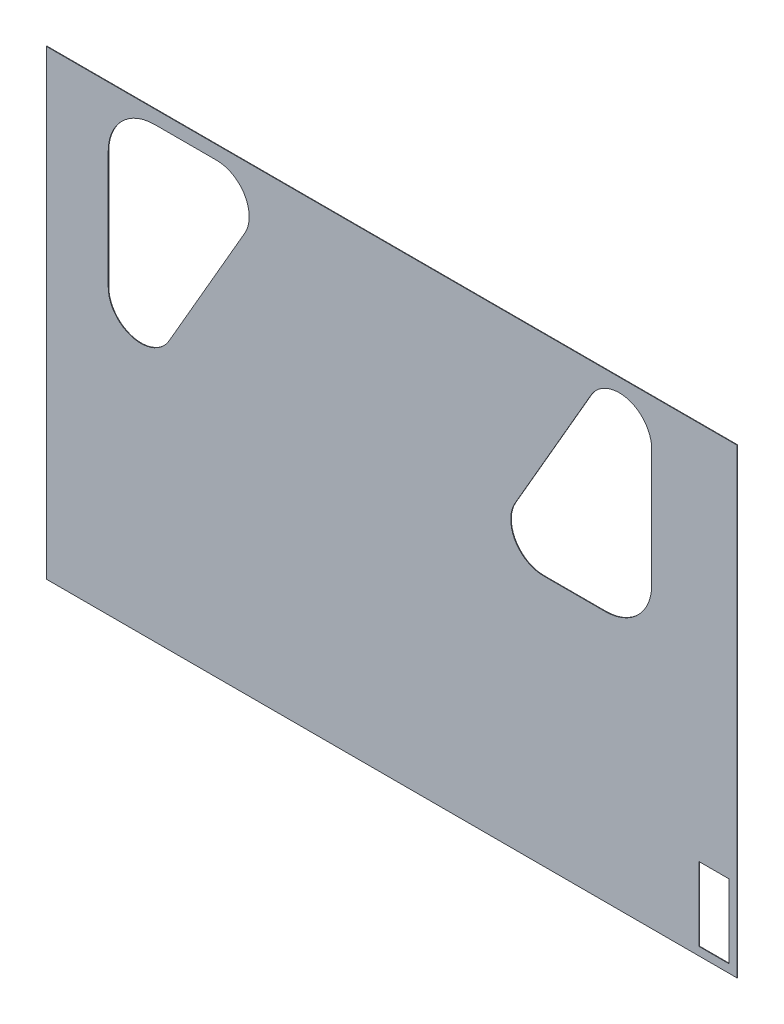
SolidWorks part; units mm, degrees
ref_plane "Front Plane" through (0, 0, 0) normal (0, 0, 1) x (1, 0, 0)
ref_plane "Top Plane" through (0, 0, 0) normal (0, 1, 0) x (1, 0, 0)
ref_plane "Right Plane" through (0, 0, 0) normal (1, 0, 0) x (0, 0, -1)
sketch "Sketch1" plane through (0, 0, 0) normal (0, 0, 1) x (1, 0, 0)
  line L1 (0, 0) -> (2500, 0)
  line L2 (0, 0) -> (0, 1670)
  line L3 (0, 1670) -> (2500, 1670)
  line L4 (2500, 0) -> (2500, 1670)
  line L5 (2470, 30) -> (2361.56, 30)
  line L6 (2470, 30) -> (2470, 296)
  line L7 (2470, 296) -> (2361.56, 296)
  line L8 (2361.56, 30) -> (2361.56, 296)
  dimension "D1" = 2500
  dimension "D2" = 1670
  dimension "D3" = 30
  dimension "D4" = 30
  dimension "D5" = 108.44
  dimension "D6" = 266
extrude "Boss-Extrude1" add sketch "Sketch1" along normal blind 2
extrude "Cut-Extrude1" cut sketch "Sketch2" against normal through all
sketch "Sketch2" plane through (471.9635, -531.6168, 33) normal (0, 0, 1) x (1, 0, 0)
  line L0 (1498.8454, 2093.6165) -> (1224.6054, 1618.6165)
  line L1 (1326.7965, 1441.6168) -> (1551.0365, 1441.6168)
  line L2 (1719.0365, 1609.6168) -> (1719.0365, 2034.6168)
  line L5 (-247.9635, 1984.6168) -> (-247.9635, 1559.6168)
  line L6 (-27.7724, 1500.617) -> (246.4676, 1975.617)
  line L7 (144.2765, 2152.6168) -> (-79.9635, 2152.6168)
  arc A0 (1551.0365, 1441.6168) -> (1719.0365, 1609.6168) centre (1551.0365, 1609.6168) ccw
  arc A1 (1498.8454, 2093.6165) -> (1719.0365, 2034.6168) centre (1601.0365, 2034.6168) cw
  arc A2 (1224.6054, 1618.6165) -> (1326.7965, 1441.6168) centre (1326.7965, 1559.6168) ccw
  arc A3 (-247.9635, 1559.6168) -> (-27.7724, 1500.617) centre (-129.9635, 1559.6168) ccw
  arc A4 (246.4676, 1975.617) -> (144.2765, 2152.6168) centre (144.2765, 2034.6168) ccw
  arc A5 (-247.9635, 1984.6168) -> (-79.9635, 2152.6168) centre (-79.9635, 1984.6168) cw
  point P22 (54.1362, 1500.617)
